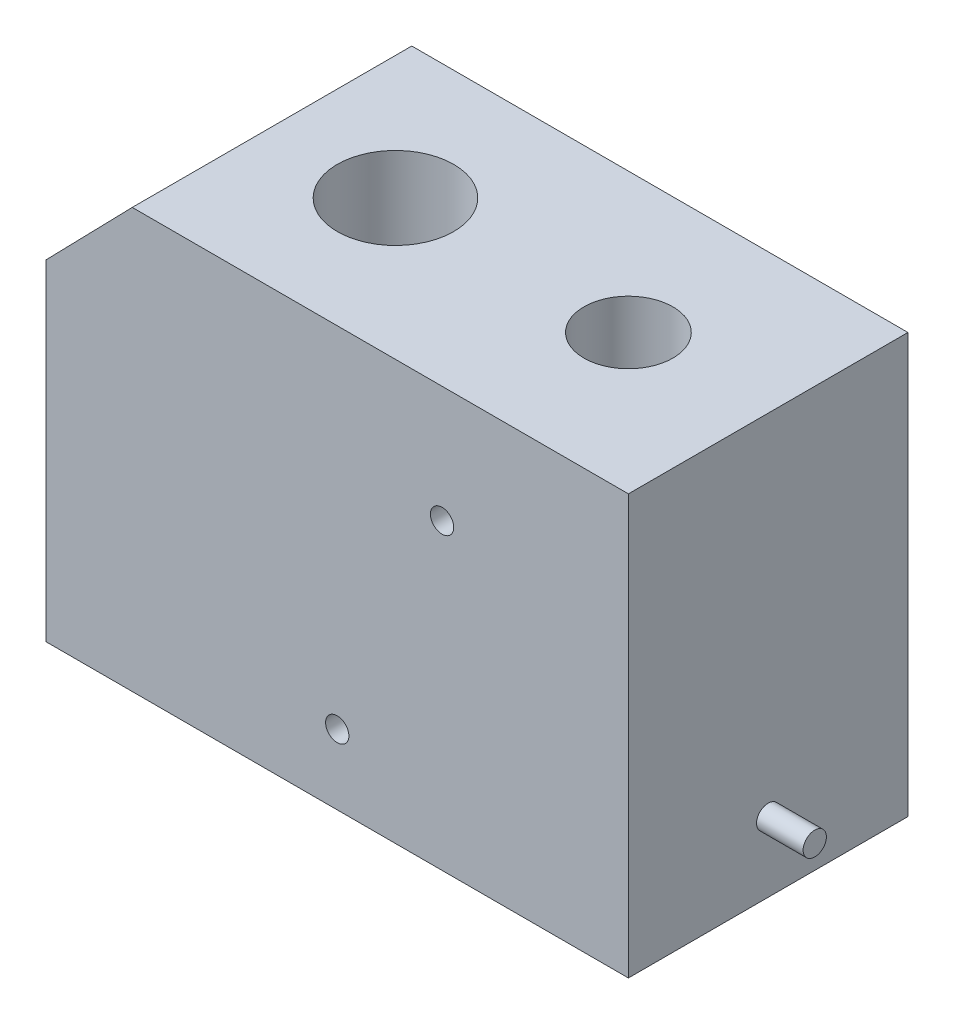
SolidWorks part; units mm, degrees
ref_plane "Front Plane" through (0, 0, 0) normal (0, 0, 1) x (1, 0, 0)
ref_plane "Top Plane" through (0, 0, 0) normal (0, 1, 0) x (1, 0, 0)
ref_plane "Right Plane" through (0, 0, 0) normal (1, 0, 0) x (0, 0, -1)
sketch "Sketch1" plane through (0, 0, 0) normal (0, 0, 1) x (1, 0, 0)
  line L1 (-125, -90) -> (125, -90)
  line L2 (-125, -90) -> (-125, 90)
  line L3 (-125, 90) -> (125, 90)
  line L4 (125, -90) -> (125, 90)
  line L5 (-125, -90) -> (125, 90) construction
  line L6 (-125, 90) -> (125, -90) construction
  point P0 (0, 0)
  dimension "D1" = 180
  dimension "D2" = 250
extrude "Boss-Extrude1" add sketch "Sketch1" along normal blind 120
sketch "Sketch2" plane through (0, 0, 120) normal (0, 0, 1) x (1, 0, 0)
  line L0 (-88, 90) -> (-125, 52)
  line L1 (125, 90) -> (-125, 90) construction
  line L2 (-125, 90) -> (-125, -90) construction
  dimension "D1" = 213
  dimension "D2" = 142
extrude "Cut-Extrude2" cut sketch "Sketch2" against normal blind 120 and the other way through all flip side to cut
sketch "Sketch3" plane through (0, 0, 120) normal (0, 0, 1) x (1, 0, 0)
  line L0 (-125, 52) -> (-125, -90) construction
  line L1 (125, 90) -> (-88, 90) construction
  circle A0 centre (45, 40) radius 5
  dimension "D3" = 10
  dimension "D1" = 170
  dimension "D2" = 50
extrude "Cut-Extrude3" cut sketch "Sketch3" against normal blind 20
sketch "Sketch4" plane through (0, 0, 120) normal (0, 0, 1) x (1, 0, 0)
  line L0 (125, 90) -> (-88, 90) construction
  line L1 (-125, 52) -> (-125, -90) construction
  circle A0 centre (0, -60) radius 5
  dimension "D3" = 10
  dimension "D1" = 150
  dimension "D2" = 125
extrude "Cut-Extrude4" cut sketch "Sketch4" against normal blind 20
sketch "Sketch5" plane through (125, 0, 0) normal (1, 0, 0) x (0, 0, -1)
  line L0 (-120, -90) -> (-120, 90) construction
  line L1 (-120, 90) -> (0, 90) construction
  circle A0 centre (-60, -60) radius 5
  dimension "D3" = 10
  dimension "D1" = 60
  dimension "D2" = 150
sketch "Sketch6" plane through (0, 0, 0) normal (0, 0, -1) x (-1, 0, 0)
  line L0 (125, 52) -> (125, -90) construction
  line L1 (125, -90) -> (-125, -90) construction
  circle A0 centre (-55, -58) radius 5
  dimension "D3" = 10
  dimension "D1" = 180
  dimension "D2" = 32
extrude "Cut-Extrude6" cut sketch "Sketch6" against normal blind 20
sketch "Sketch7" plane through (0, -90, 0) normal (0, -1, 0) x (1, 0, 0)
  line L0 (125, 120) -> (125, 0) construction
  line L1 (-125, 0) -> (125, 0) construction
  circle A0 centre (-35, 60) radius 25
  dimension "D3" = 50
  dimension "D1" = 160
  dimension "D2" = 60
extrude "Cut-Extrude7" cut sketch "Sketch7" against normal through all
extrude "Boss-Extrude2" add sketch "Sketch5" along normal blind 20 contours A0
hole_wizard "Ø10.0mm Dowel Hole1" positions "3DSketch1" profile "Sketch8" hole size "Ø10.0" standard "ISO"
sketch3d "3DSketch1"
  line L0 (-125, 52, 120) -> (-125, -90, 120) construction
  line L1 (-125, -90, 120) -> (-125, -90, 0) construction
  point P0 (-125, -43, 98)
  dimension "D1" = 22
  dimension "D2" = 47
sketch "Sketch8" plane through (-125, -43, 98) normal (0, 1, 0) x (0, 0, 1)
  line L0 (0, 0) -> (0, 23.0043)
  line L1 (0, 23.0043) -> (5, 20)
  line L2 (5, 20) -> (5, 0)
  line L5 (5, 0) -> (0, 0)
  line L10 (0, 23.0043) -> (-5, 20) construction
  line L11 (0, -6.35) -> (0, 107.95) construction
  dimension "Hole Dia." = 10
  dimension "Hole Depth" = 20
  dimension "Drill Angle" = 118
sketch "Sketch9" plane through (0, 90, 0) normal (0, 1, 0) x (1, 0, 0)
  line L0 (125, -120) -> (-88, -120) construction
  circle A0 centre (65, -60) radius 19.0948
  circle A1 centre (-35, -60) radius 25 construction
  dimension "D1" = 100
  dimension "D2" = 60
extrude "Cut-Extrude8" cut sketch "Sketch9" against normal blind 50
